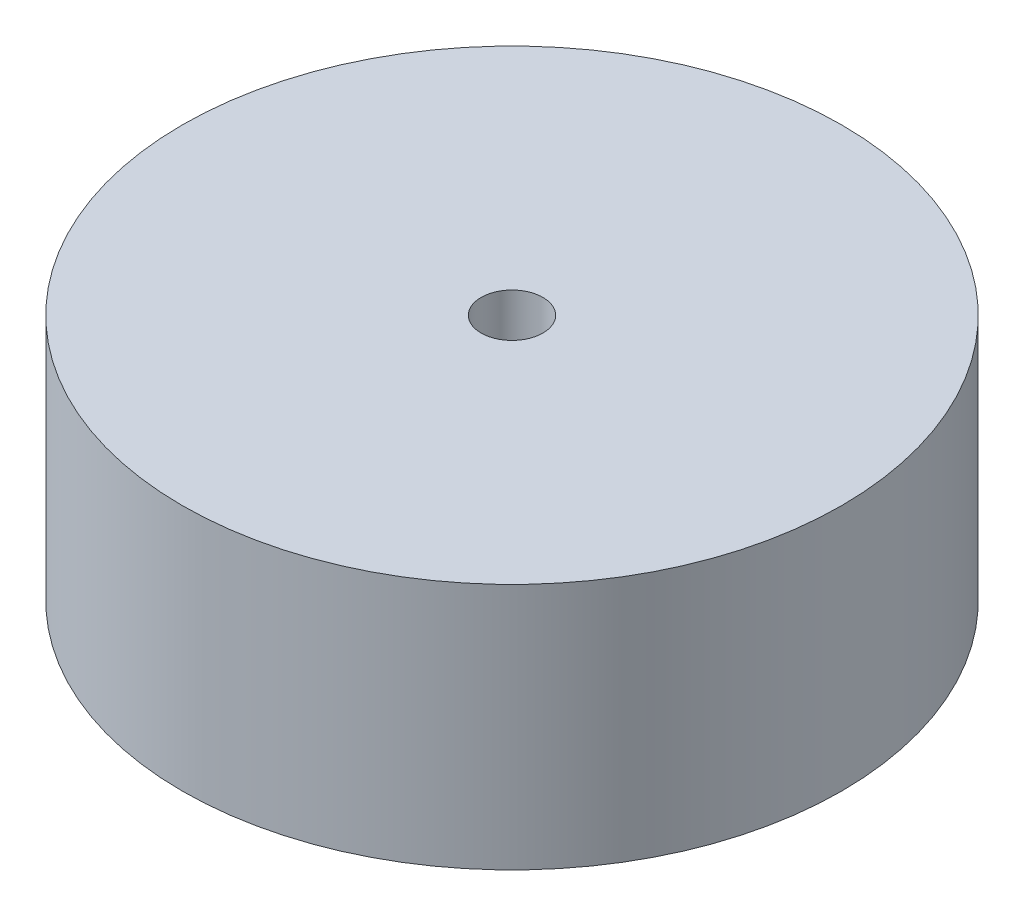
SolidWorks part; units mm, degrees
ref_plane "Front Plane" through (0, 0, 0) normal (0, 0, 1) x (1, 0, 0)
ref_plane "Top Plane" through (0, 0, 0) normal (0, 1, 0) x (1, 0, 0)
ref_plane "Right Plane" through (0, 0, 0) normal (1, 0, 0) x (0, 0, -1)
sketch "Sketch1" plane through (0, 0, 0) normal (0, 1, 0) x (1, 0, 0)
  circle A0 centre (0, 0) radius 101.6
  dimension "D1" = 203.2
extrude "Boss-Extrude1" add sketch "Sketch1" along normal blind 76.2
sketch "Sketch2" plane through (0, 76.2, 0) normal (0, 1, 0) x (1, 0, 0)
  circle A0 centre (0, 0) radius 9.525
  dimension "D1" = 19.05
extrude "Cut-Extrude1" cut sketch "Sketch2" against normal through all
